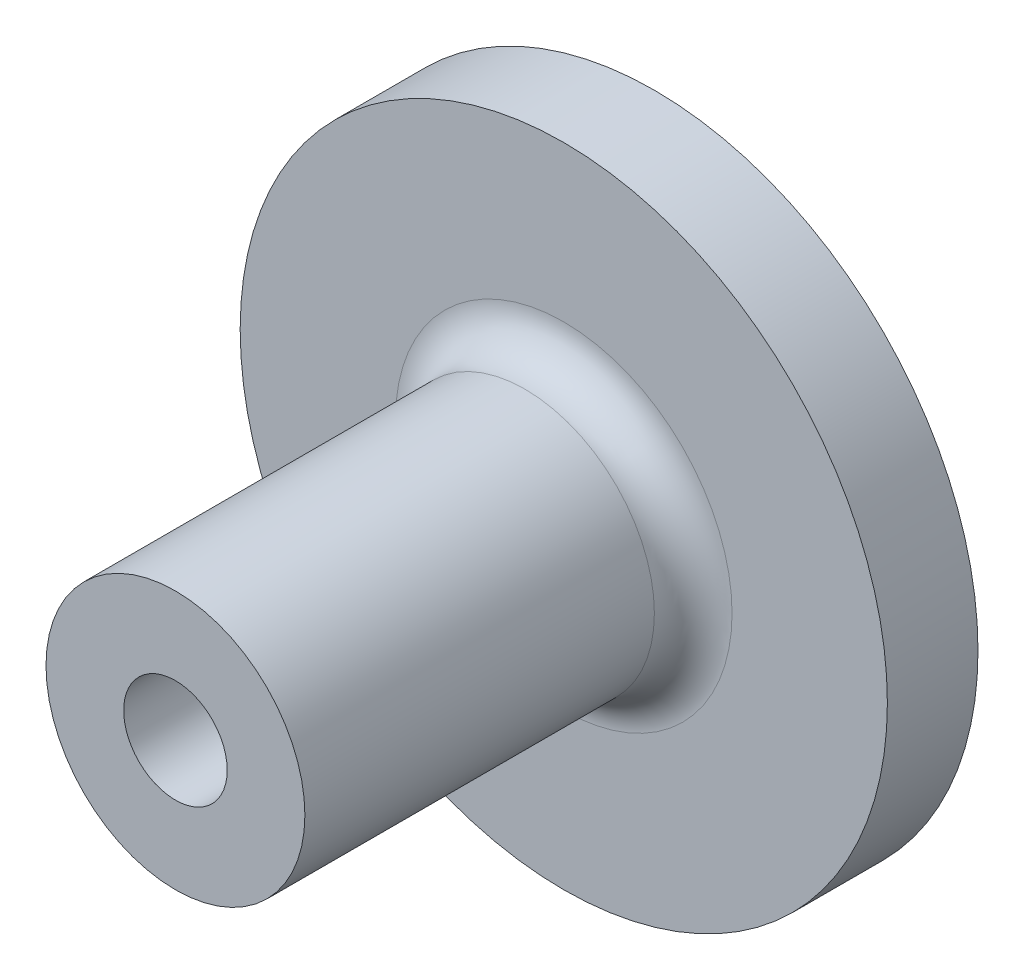
SolidWorks part; units mm, degrees
ref_plane "Спереди" through (0, 0, 0) normal (0, 0, 1) x (1, 0, 0)
ref_plane "Сверху" through (0, 0, 0) normal (0, 1, 0) x (1, 0, 0)
ref_plane "Справа" through (0, 0, 0) normal (1, 0, 0) x (0, 0, -1)
sketch "Эскиз1" plane through (0, 0, 0) normal (0, 0, 1) x (1, 0, 0)
  circle A0 centre (0, 0) radius 25
extrude "Вытянуть1" add sketch "Эскиз1" along normal blind 7
sketch "Эскиз2" plane through (0, 0, 7) normal (0, 0, 1) x (1, 0, 0)
  circle A0 centre (0, 0) radius 10
extrude "Вытянуть2" add sketch "Эскиз2" along normal blind 30
fillet "Скругление1" radius 3 1 edges at (10, 0, 7)
sketch "Эскиз3" plane through (0, 0, 37) normal (0, 0, 1) x (1, 0, 0)
  circle A0 centre (0, 0) radius 4
extrude "Вытянуть3" cut sketch "Эскиз3" against normal through all
